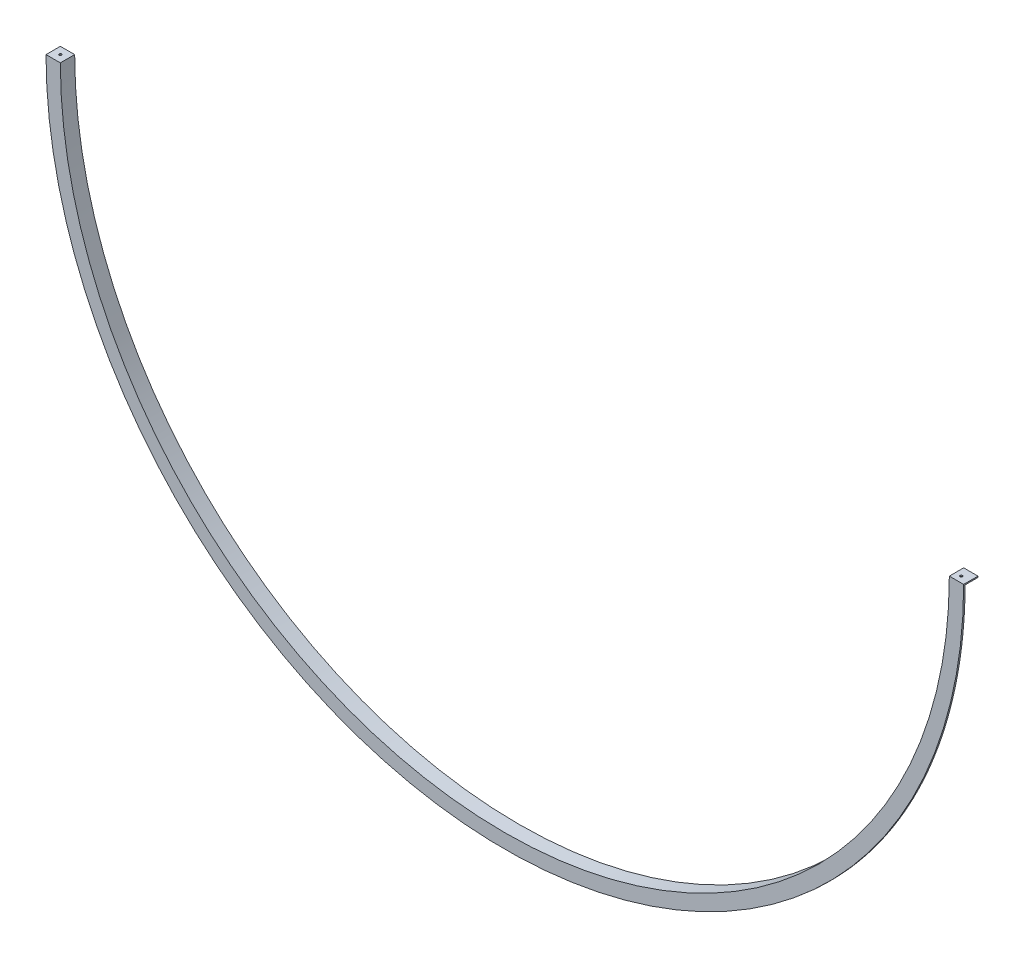
SolidWorks part; units mm, degrees
material "ASTM A36 Steel"
ref_plane "Front Plane" through (0, 0, 0) normal (0, 0, 1) x (1, 0, 0)
ref_plane "Top Plane" through (0, 0, 0) normal (0, 1, 0) x (1, 0, 0)
ref_plane "Right Plane" through (0, 0, 0) normal (1, 0, 0) x (0, 0, -1)
sketch "Sketch1" plane through (0, 0, 0) normal (0, 1, 0) x (1, 0, 0)
  line L0 (0, 0) -> (48.0645, 0)
  line L1 (48.0645, 0) -> (48.0645, 4.8065)
  line L2 (48.0645, 4.8065) -> (4.8065, 4.8065)
  line L3 (4.8065, 4.8065) -> (4.8065, 48.0645)
  line L4 (4.8065, 48.0645) -> (0, 48.0645)
  line L5 (0, 48.0645) -> (0, 0)
  line L7 (-1490, 0) -> (-1490, 275.967) construction
  dimension "D1" = 1490
revolve "Revolve1" add sketch "Sketch1" angle 180 about L7
sketch "Sketch4" plane through (0, 0, 0) normal (0, 1, 0) x (1, 0, 0)
  line L0 (0, 0) -> (48.0645, 0)
  line L1 (-2980, 0) -> (-3028, 0)
  line L2 (-2980, 0) -> (-2980, 48)
  line L3 (-2980, 48) -> (-3028, 48)
  line L4 (-3028, 0) -> (-3028, 48)
  line L5 (48.0645, 0) -> (48.0645, 48.0645)
  line L6 (48.0645, 48.0645) -> (0, 48.0645)
  line L7 (0, 48.0645) -> (0, 0)
  circle A0 centre (-3004, 24.0323) radius 4
  circle A1 centre (20, 20) radius 4
  point P16 (-2931.3126, -10.4383)
  point P17 (-3004, 24.0323)
  dimension "D1" = 48
  dimension "D2" = 48
extrude "Boss-Extrude1" add sketch "Sketch4" against normal blind 4
